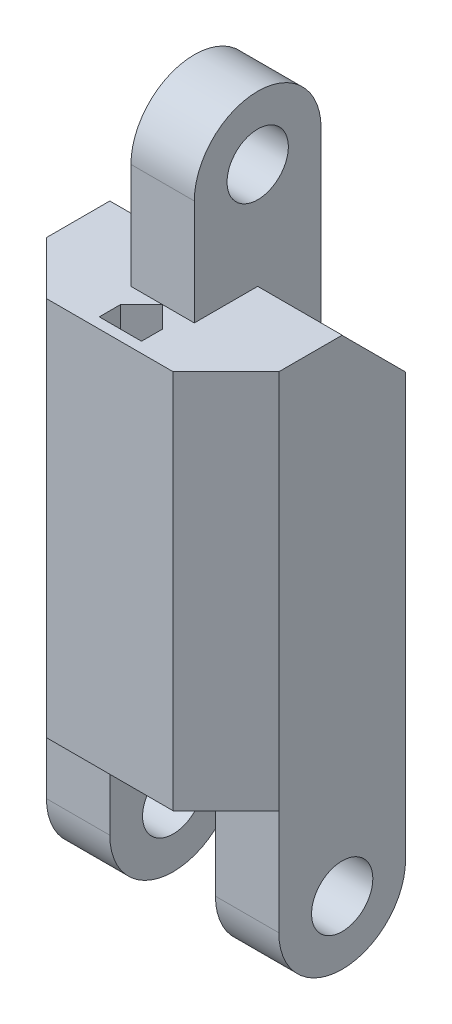
SolidWorks part; units mm, degrees
ref_plane "Front Plane" through (0, 0, 0) normal (0, 0, 1) x (1, 0, 0)
ref_plane "Top Plane" through (0, 0, 0) normal (0, 1, 0) x (1, 0, 0)
ref_plane "Right Plane" through (0, 0, 0) normal (1, 0, 0) x (0, 0, -1)
sketch "Sketch2" plane through (0, 0, 0) normal (0, 1, 0) x (1, 0, 0)
  line L0 (-3, 5.5) -> (3, 5.5)
  line L1 (3, 5.5) -> (5.5, 3)
  line L2 (5.5, 3) -> (5.5, -3)
  line L3 (5.5, -3) -> (3, -5.5)
  line L4 (3, -5.5) -> (-3, -5.5)
  line L5 (-3, -5.5) -> (-5.5, -3)
  line L6 (-5.5, -3) -> (-5.5, 3)
  line L7 (-5.5, 3) -> (-3, 5.5)
  point P2 (0, -5.5)
  point P9 (0, 5.5)
  point P11 (2.6457, 8.1898)
  point P12 (-5.5, 0)
  point P13 (5.5, 0)
  dimension "D1" = 11
  dimension "D2" = 11
  dimension "D3" = 6
  dimension "D4" = 6
  dimension "D5" = 6
extrude "Boss-Extrude1" add sketch "Sketch2" along normal mid plane 18 contours L7 L0 L1 L2 L3 L4 L5 L6
sketch "Sketch5" plane through (0, 0, 0) normal (1, 0, 0) x (0, 0, -1)
  line L0 (0, 9) -> (0, 8.99)
  line L1 (3, 9) -> (-3, 9) construction
  line L2 (0, 8.99) -> (5.5, 3.49)
  line L3 (5.5, 9) -> (5.5, -9) construction
  line L4 (5.5, 3.49) -> (5.5, 9)
  line L5 (5.5, 9) -> (0, 9)
  point P4 (0, 9)
  dimension "D2" = 0.01
  dimension "D3" = 135
extrude "Cut-Extrude2" cut sketch "Sketch5" against normal through all both and the other way through all
mirror "Mirror3" about plane through (0, 0, 0) normal (0, 1, 0) of "Cut-Extrude2"
sketch "Sketch6" plane through (0, -9, 0) normal (0, -1, 0) x (1, 0, 0)
  line L1 (-5.5, 3) -> (-2.5, 3)
  line L2 (-5.5, 3) -> (-5.5, -3)
  line L3 (-5.5, -3) -> (-2.5, -3)
  line L4 (-2.5, 3) -> (-2.5, -3)
  dimension "D1" = 3
extrude "Boss-Extrude3" add sketch "Sketch6" along normal mid plane 10
sketch "Sketch7" plane through (0, -14, 0) normal (0, -1, 0) x (1, 0, 0)
  line L0 (-5.5, 3) -> (-5.5, -3) construction
  line L1 (-5.5, 0) -> (-2.5, 0)
  line L2 (-5.5, 0) -> (-5.5, 3)
  line L3 (-5.5, 3) -> (-2.5, 3)
  line L4 (-2.5, 0) -> (-2.5, 3)
revolve "Revolve1" add sketch "Sketch7" angle 180 about L1
sketch "Sketch8" plane through (-5.5, 0, 0) normal (-1, 0, 0) x (0, 0, 1)
  line L0 (-3, -14) -> (3, -14) construction
sketch "Sketch9" plane through (-5.5, 0, 0) normal (-1, 0, 0) x (0, 0, 1)
  line L0 (-3, -14) -> (3, -14) construction
  circle A0 centre (0, -14) radius 1.45
  dimension "D1" = 2.9
extrude "Cut-Extrude3" cut sketch "Sketch9" against normal mid plane 10
mirror "Mirror5" about plane through (0, 0, 0) normal (1, 0, 0) of "Revolve1", "Boss-Extrude3", "Cut-Extrude3"
sketch "Sketch10" plane through (0, 9, 0) normal (0, 1, 0) x (1, 0, 0)
  line L0 (-5.5, -3) -> (5.5, -3) construction
  line L1 (-1.5, -3) -> (1.5, -3)
  line L2 (-1.5, -3) -> (-1.5, 3)
  line L3 (-1.5, 3) -> (1.5, 3)
  line L4 (1.5, -3) -> (1.5, 3)
  line L5 (-1.5, -3) -> (1.5, 3) construction
  line L6 (-1.5, 3) -> (1.5, -3) construction
  point P6 (0, 0)
  dimension "D1" = 3
extrude "Boss-Extrude4" add sketch "Sketch10" along normal mid plane 10
sketch "Sketch12" plane through (0, 14, 0) normal (0, 1, 0) x (1, 0, 0)
  line L1 (-1.5, 0) -> (1.5, 0)
  line L2 (-1.5, 0) -> (-1.5, 3)
  line L3 (-1.5, 3) -> (1.5, 3)
  line L4 (1.5, 0) -> (1.5, 3)
revolve "Revolve2" add sketch "Sketch12" angle 180 about L1
sketch "Sketch13" plane through (-1.5, 0, 0) normal (-1, 0, 0) x (0, 0, 1)
  line L0 (-3, 14) -> (3, 14) construction
sketch "Sketch14" plane through (-1.5, 0, 0) normal (-1, 0, 0) x (0, 0, 1)
  line L0 (-3, 14) -> (3, 14) construction
  circle A0 centre (0, 14) radius 1.45
  dimension "D1" = 2.9
extrude "Cut-Extrude4" cut sketch "Sketch14" against normal mid plane 10
sketch "Sketch15" plane through (0, 0, 0) normal (0, 1, 0) x (1, 0, 0)
  line L0 (0, 5) -> (-1, 4)
  line L1 (-1, 4) -> (-1, 3)
  line L2 (-1, 3) -> (1, 3)
  line L3 (1, 3) -> (1, 4)
  line L4 (1, 4) -> (0, 5)
  line L5 (1.5, 3) -> (-1.5, 3) construction
  line L6 (1, -4) -> (0, -3)
  line L7 (0, -3) -> (-1, -4)
  line L8 (-1, -4) -> (-1, -5)
  line L9 (-1, -5) -> (1, -5)
  line L10 (1, -5) -> (1, -4)
  line L11 (-1.5, -3) -> (1.5, -3) construction
  point P8 (0, 0)
  dimension "D1" = 2
  dimension "D2" = 2
  dimension "D3" = 135
  dimension "D4" = 135
  dimension "D5" = 1
  dimension "D6" = 2
extrude "Cut-Extrude5" cut sketch "Sketch15" against normal through all both and the other way through all
